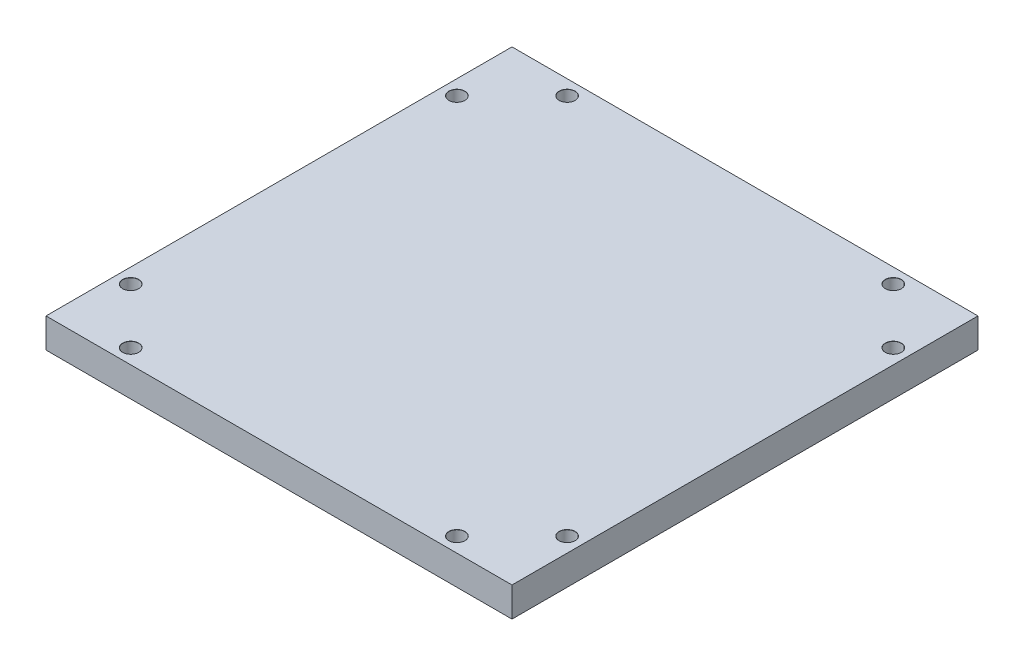
SolidWorks part; units mm, degrees
material "6061 Alloy"
ref_plane "Front Plane" through (0, 0, 0) normal (0, 0, 1) x (1, 0, 0)
ref_plane "Top Plane" through (0, 0, 0) normal (0, 1, 0) x (1, 0, 0)
ref_plane "Right Plane" through (0, 0, 0) normal (1, 0, 0) x (0, 0, -1)
sketch "Sketch1" plane through (0, 0, 0) normal (0, 1, 0) x (1, 0, 0)
  line L1 (-50, -50) -> (50, -50)
  line L2 (-50, -50) -> (-50, 50)
  line L3 (-50, 50) -> (50, 50)
  line L4 (50, -50) -> (50, 50)
  line L5 (-50, -50) -> (50, 50) construction
  line L6 (-50, 50) -> (50, -50) construction
extrude "Boss-Extrude3" add sketch "Sketch1" along normal blind 6.35
sketch "Sketch8" plane through (0, 6.35, 0) normal (0, 1, 0) x (1, 0, 0)
  line L0 (-50, -50) -> (-39.5, -50)
  line L1 (-50, -50) -> (50, -50) construction
  line L2 (-39.5, -50) -> (-39.5, -39.5)
  line L3 (50, -50) -> (39.5, -50)
  line L4 (39.5, -50) -> (39.5, -39.5)
  line L5 (50, 50) -> (39.5, 50)
  line L6 (-50, 50) -> (50, 50) construction
  line L7 (39.5, 50) -> (39.5, 39.5)
  line L8 (-50, 50) -> (-39.5, 50)
  line L9 (-50, -50) -> (-50, 50) construction
  line L10 (-39.5, 50) -> (-39.5, 39.5)
sketch "Sketch13" plane through (0, 6.35, 0) normal (0, 1, 0) x (1, 0, 0)
  line L1 (-50, -50) -> (-35, -50)
  line L2 (-50, -50) -> (50, -50) construction
  line L3 (-35, -50) -> (-35, -46.825)
  line L4 (-50, -50) -> (-50, -35)
  line L5 (-50, -50) -> (-50, 50) construction
  line L6 (-50, -35) -> (-46.825, -35)
  line L7 (-50, 50) -> (-35, 50)
  line L8 (-50, 50) -> (50, 50) construction
  line L9 (-35, 50) -> (-35, 46.825)
  line L10 (-50, 50) -> (-50, 35)
  line L11 (-50, 35) -> (-46.825, 35)
  line L13 (50, 50) -> (35, 50)
  line L14 (35, 50) -> (35, 46.825)
  line L15 (50, 50) -> (50, 35)
  line L16 (50, -50) -> (50, 50) construction
  line L17 (50, 35) -> (46.825, 35)
  line L18 (50, -50) -> (50, -35)
  line L19 (50, -35) -> (46.825, -35)
  line L20 (50, -50) -> (35, -50)
  line L21 (35, -50) -> (35, -46.825)
hole_wizard "M3 Clearance Hole1" positions "Sketch17" profile "Sketch18" hole size "M3" standard "ANSI Metric" end condition through all
sketch "Sketch17" plane through (0, 6.35, 0) normal (0, 1, 0) x (1, 0, 0)
  point P0 (-46.825, 35)
  point P3 (-35, 46.825)
  point P6 (35, 46.825)
  point P9 (46.825, 35)
  point P12 (46.825, -35)
  point P15 (35, -46.825)
  point P18 (-35, -46.825)
  point P21 (-46.825, -35)
sketch "Sketch18" plane through (-46.825, 6.35, -35) normal (1, 0, 0) x (0, 0, 1)
  line L0 (0, 0) -> (0, 6.35)
  line L1 (0, 6.35) -> (1.7, 6.35)
  line L2 (1.7, 6.35) -> (1.7, 0.025)
  line L3 (1.7, 0.025) -> (1.725, 0)
  line L5 (1.725, 0) -> (0, 0)
  line L6 (-1.7, 0.025) -> (-1.725, 0) construction
  line L11 (0, -6.35) -> (0, 107.95) construction
  dimension "Thru Hole Dia." = 3.4
  dimension "Thru Hole Depth" = 6.35
  dimension "Near C'Sink Dia." = 3.45
  dimension "Near C'Sink Angle" = 90
